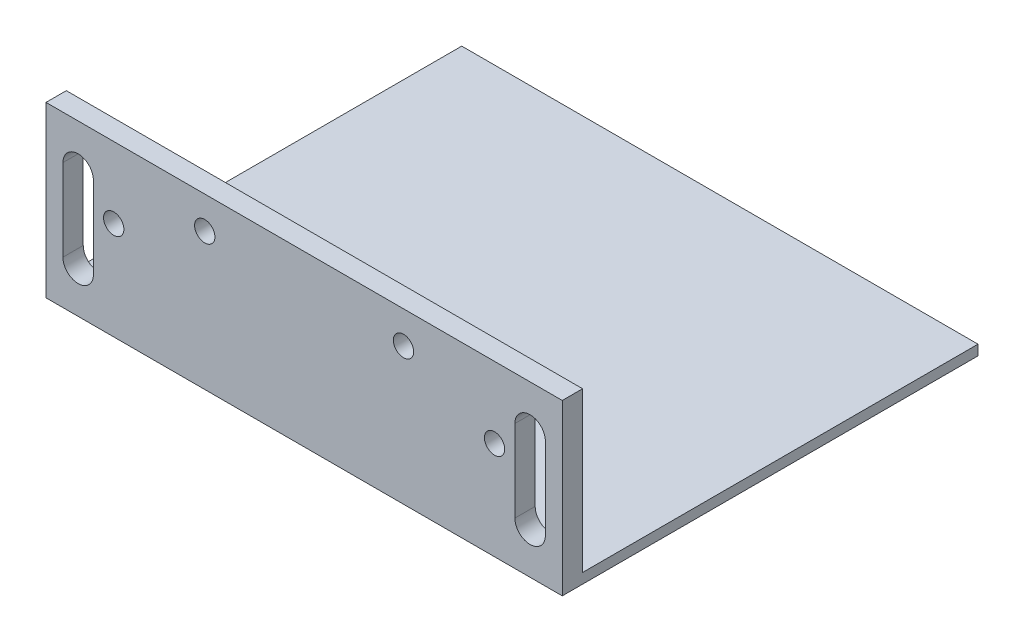
SolidWorks part; units mm, degrees
ref_plane "Front Plane" through (0, 0, 0) normal (0, 0, 1) x (1, 0, 0)
ref_plane "Top Plane" through (0, 0, 0) normal (0, 1, 0) x (1, 0, 0)
ref_plane "Right Plane" through (0, 0, 0) normal (1, 0, 0) x (0, 0, -1)
sketch "Sketch1" plane through (0, 0, 0) normal (0, 1, 0) x (1, 0, 0)
  line L1 (38.125, -29.2) -> (-38.125, -29.2)
  line L2 (38.125, -29.2) -> (38.125, 29.2)
  line L3 (38.125, 29.2) -> (-38.125, 29.2)
  line L4 (-38.125, -29.2) -> (-38.125, 29.2)
  line L5 (38.125, -29.2) -> (-38.125, 29.2) construction
  line L6 (38.125, 29.2) -> (-38.125, -29.2) construction
  point P0 (0, 0)
  point P6 (13.3208, -15.9456)
  point P7 (0, 0)
  point P8 (0, 0)
  point P9 (-38.125, 16.8642)
  dimension "D1" = 76.25
  dimension "D2" = 58.4
extrude "Boss-Extrude1" add sketch "Sketch1" along normal blind 1.5
sketch "Sketch2" plane through (0, 0, 29.2) normal (0, 0, 1) x (1, 0, 0)
  line L0 (38.125, 1.5) -> (38.125, 0) construction
  line L1 (-38.125, 0) -> (38.125, 0)
  line L2 (-38.125, 0) -> (-38.125, 25)
  line L3 (-38.125, 25) -> (38.125, 25)
  line L4 (38.125, 0) -> (38.125, 25)
  dimension "D1" = 25
extrude "Boss-Extrude2" add sketch "Sketch2" along normal blind 3
sketch "Sketch3" plane through (0, 0, 32.2) normal (0, 0, 1) x (1, 0, 0)
  line L0 (-33.375, 18.55) -> (-33.375, 6.45) construction
  line L1 (-31.125, 18.55) -> (-31.125, 6.45)
  line L2 (-35.625, 18.55) -> (-35.625, 6.45)
  line L3 (-38.125, 25) -> (-38.125, 0) construction
  line L4 (38.125, 25) -> (-38.125, 25) construction
  line L5 (-38.125, 0) -> (38.125, 0) construction
  circle A0 centre (-28.125, 14.5) radius 1.5
  circle A1 centre (-14.6781, 20.2476) radius 1.5
  arc A2 (-31.125, 18.55) -> (-35.625, 18.55) centre (-33.375, 18.55) ccw
  arc A3 (-35.625, 6.45) -> (-31.125, 6.45) centre (-33.375, 6.45) ccw
  point P6 (-33.375, 12.5)
  dimension "D2" = 3
  dimension "D7" = 10
  dimension "D1" = 4.5
  dimension "D3" = 2.5
  dimension "D4" = 6.45
  dimension "D5" = 6.45
  dimension "D6" = 10.5
extrude "Cut-Extrude1" cut sketch "Sketch3" against normal through all
mirror "Mirror1" about plane through (0, 0, 0) normal (1, 0, 0) of "Cut-Extrude1"
